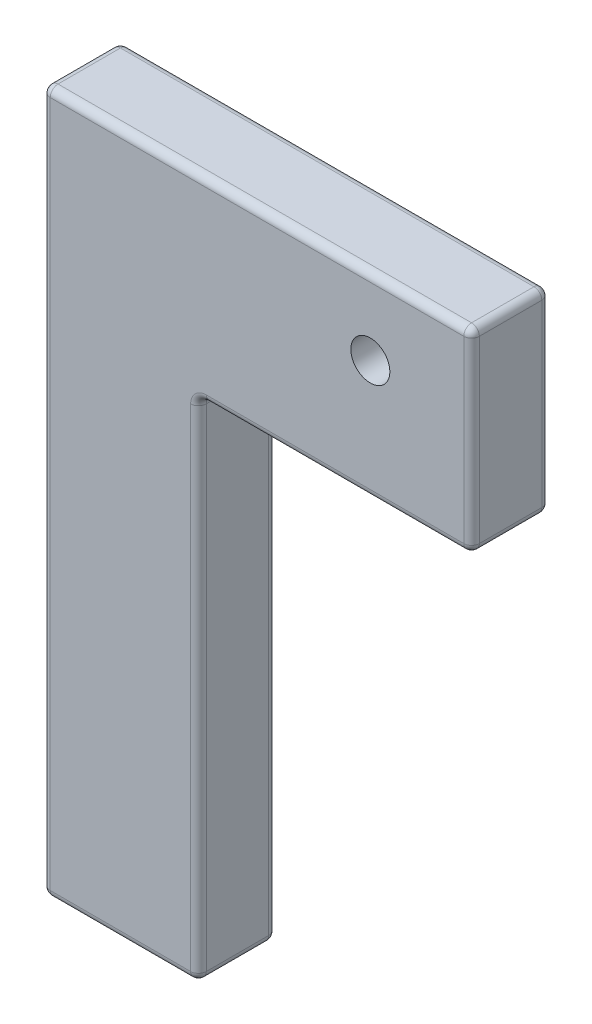
SolidWorks part; units mm, degrees
ref_plane "Front Plane" through (0, 0, 0) normal (0, 0, 1) x (1, 0, 0)
ref_plane "Top Plane" through (0, 0, 0) normal (0, 1, 0) x (1, 0, 0)
ref_plane "Right Plane" through (0, 0, 0) normal (1, 0, 0) x (0, 0, -1)
sketch "Sketch2" plane through (0, 0, 0) normal (0, 0, 1) x (1, 0, 0)
  line L0 (0, 0) -> (0, 90)
  line L3 (55, 65) -> (20, 65)
  line L4 (20, 65) -> (20, 0)
  line L5 (20, 0) -> (0, 0)
  line L6 (0, 90) -> (55, 90)
  line L9 (55, 90) -> (55, 65)
  circle A0 centre (42.0256, 80.3293) radius 2.5
  dimension "D1" = 90
  dimension "D2" = 25
  dimension "D3" = 20
  dimension "D4" = 35
extrude "Boss-Extrude1" add sketch "Sketch2" along normal blind 10
fillet "Fillet1" radius 1 18 edges at (37.5, 65, 0) (20, 32.5, 0) (27.5, 90, 0) (10, 0, 10) (20, 32.5, 10) (37.5, 65, 10) (27.5, 90, 10) (0, 45, 10) (0, 90, 5) (20, 65, 5) (20, 0, 5) (55, 65, 5) (55, 90, 5) (0, 0, 5) (55, 77.5, 10) (0, 45, 0) (55, 77.5, 0) (10, 0, 0)
